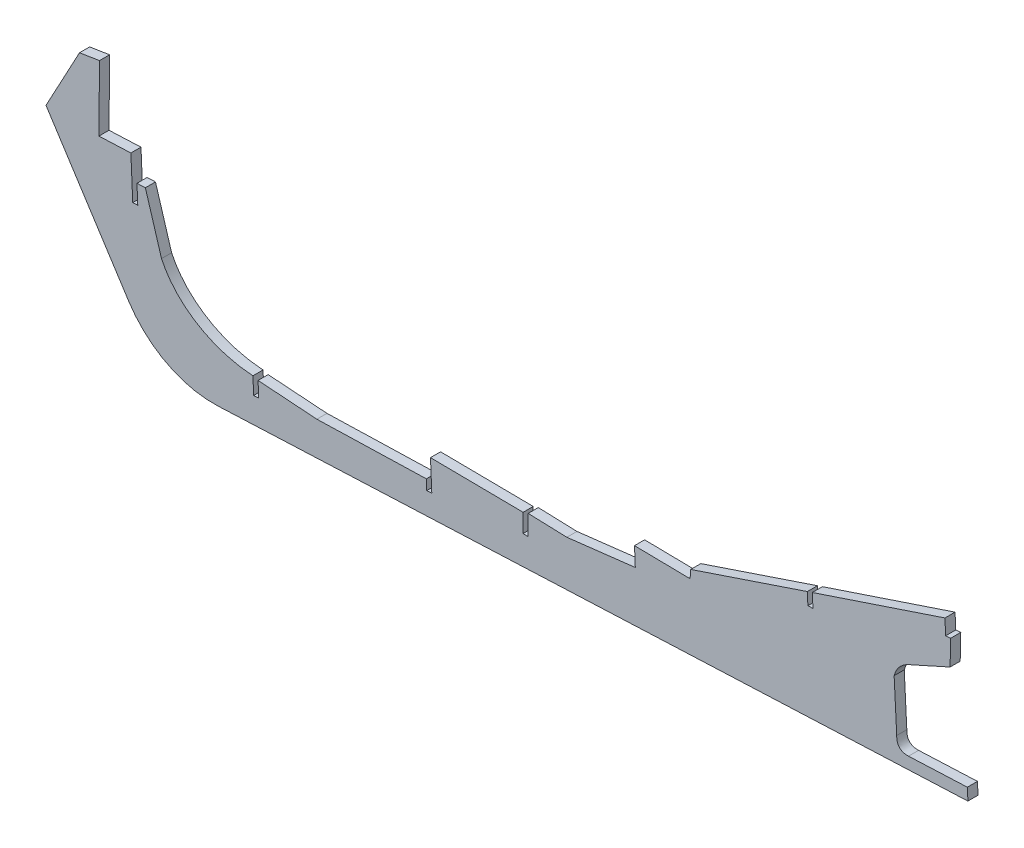
SolidWorks part; units mm, degrees
ref_plane "Plan de face" through (0, 0, 0) normal (0, 0, 1) x (1, 0, 0)
ref_plane "Plan de dessus" through (0, 0, 0) normal (0, 1, 0) x (1, 0, 0)
ref_plane "Plan de droite" through (0, 0, 0) normal (1, 0, 0) x (0, 0, -1)
sketch "Esquisse1" plane through (0, 0, 0) normal (0, 1, 0) x (1, 0, 0)
  point P0 (0, 27.1237)
sketch3d "Esquisse3D1" [suppressed]
sketch "Esquisse2" [suppressed] plane through (0, 0, -27.1237) normal (0, 0, 1) x (1, 0, 0)
  line L1 (-19.7278, 59.5167) -> (107.672, 59.5167)
  line L2 (-19.7278, 59.5167) -> (-19.7278, -11.328)
  line L3 (-19.7278, -11.328) -> (107.672, -11.328)
  line L4 (107.672, 59.5167) -> (107.672, -11.328)
extrude "Boss.-Extru.2" [suppressed] add sketch "Esquisse2" along normal blind 1 contours L1 L4 L3 L2
sketch "Esquisse3" plane through (-3.6383, 7.7629, 0) normal (0, 0, 1) x (0.9848, -0.1736, 0)
  line L0 (-71.5597, 137.4195) -> (-65.1276, 98.9536)
  line L1 (-65.1276, 98.9536) -> (-46.5785, 103.0681)
  line L2 (-46.5785, 103.0681) -> (-41.1646, 78.6613)
  line L3 (-41.1646, 78.6613) -> (-38.2358, 79.311)
  line L4 (-38.2358, 79.311) -> (-40.6324, 90.1151)
  line L5 (-40.6324, 90.1151) -> (-35.751, 91.1979)
  line L6 (-35.751, 91.1979) -> (-20.8298, 61.6864)
  line L7 (38.3746, 38.5134) -> (40.5254, 28.8169)
  line L8 (40.5254, 28.8169) -> (43.4639, 29.4213)
  line L9 (43.4639, 29.4213) -> (41.5196, 38.1867)
  line L11 (139.998, 54.9094) -> (141.2836, 49.114)
  line L12 (141.2836, 49.114) -> (144.2124, 49.7636)
  line L13 (144.2124, 49.7636) -> (140.3282, 67.2743)
  line L14 (140.3282, 67.2743) -> (194.5928, 76.2383)
  line L15 (194.5928, 76.2383) -> (196.4096, 65.3893)
  line L16 (196.4096, 65.3893) -> (199.3684, 65.8848)
  line L17 (199.3684, 65.8848) -> (197.394, 77.6747)
  line L18 (197.394, 77.6747) -> (220.1265, 80.8778)
  line L19 (220.1265, 80.8778) -> (259.3198, 92.6445)
  line L20 (259.3198, 92.6445) -> (256.9377, 103.3834)
  line L25 (289.5225, 108.6015) -> (289.0475, 113.5789)
  line L36 (406.9571, 140.2014) -> (413.6678, 110.9615)
  line L37 (421.7867, 105.1235) -> (455.9562, 112.7029)
  line L38 (455.9562, 112.7029) -> (457.472, 105.869)
  line L39 (457.472, 105.869) -> (159.7095, 39.82)
  line L40 (159.7095, 39.82) -> (-11.1378, 1.923)
  line L42 (-82.903, 133.5043) -> (-71.5597, 137.4195)
  line L44 (-82.903, 133.5043) -> (-96.0826, 93.6257)
  line L45 (-96.0826, 93.6257) -> (-11.1378, 1.923)
  line L47 (256.9377, 103.3834) -> (289.5225, 108.6015)
  line L50 (415.3421, 152.6389) -> (436.0141, 166.6984)
  line L51 (436.0141, 166.6984) -> (433.7399, 181.525)
  line L52 (433.7399, 181.525) -> (430.8448, 180.7389)
  line L53 (430.8448, 180.7389) -> (428.8958, 189.5254)
  line L54 (353.1813, 148.4854) -> (289.0475, 113.5789)
  line L55 (41.5196, 38.1867) -> (76.3314, 41.8113)
  line L56 (76.3314, 41.8113) -> (139.998, 54.9094)
  line L57 (355.9232, 149.9778) -> (357.6557, 142.1676)
  line L58 (357.6557, 142.1676) -> (354.7269, 141.518)
  line L59 (354.7269, 141.518) -> (353.1813, 148.4854)
  line L60 (428.8958, 189.5254) -> (355.9232, 149.9778)
  spline S0 degree 3 poles (38.3746, 38.5134) (16.5878, 35.9393) (-7.7627, 43.297) (-20.8298, 61.6864) knots 0 0 0 0 1 1 1 1
  spline S4 degree 2 poles (415.3421, 152.6389) (407.5453, 148.0093) (406.9571, 140.2014) knots 0 0 0 1 1 1
  spline S5 degree 2 poles (413.6678, 110.9615) (414.7661, 103.7369) (421.7867, 105.1235) knots 0 0 0 1 1 1
  dimension "D18" = 15
  dimension "D1" = 12
  dimension "D2" = 42
  dimension "D3" = 39
  dimension "D4" = 19
  dimension "D5" = 3
  dimension "D6" = 5
  dimension "D7" = 3
  dimension "D8" = 125
  dimension "D9" = 65
  dimension "D10" = 3
  dimension "D11" = 55
  dimension "D12" = 175
  dimension "D13" = 7
  dimension "D14" = 35
  dimension "D15" = 305
  dimension "D16" = 10
  dimension "D17" = 30
  dimension "D19" = 25
  dimension "D20" = 3
  dimension "D21" = 11
  dimension "D22" = 27
  dimension "D23" = 3
  dimension "D24" = 41
  dimension "D25" = 33
  dimension "D26" = 5
  dimension "D27" = 15
  dimension "D28" = 3
  dimension "D29" = 9
  dimension "D30" = 159.1396
  dimension "D31" = 24
  dimension "D32" = 19
  dimension "D33" = 31
  dimension "D34" = 28
  dimension "D36" = 79
  dimension "D37" = 87.8596
  dimension "D38" = 25
  dimension "D39" = 144
  dimension "D40" = 30
  dimension "D41" = 20
  dimension "D42" = 35
  dimension "D43" = 3
  dimension "D44" = 25
  dimension "D45" = 83
  dimension "D46" = 8
extrude "Boss.-Extru.3" add sketch "Esquisse3" along normal blind 6
scale "Echelle1" [suppressed]
fillet "Congé1" radius 60 1 edges at (-14.273, 11.5907, 3)
